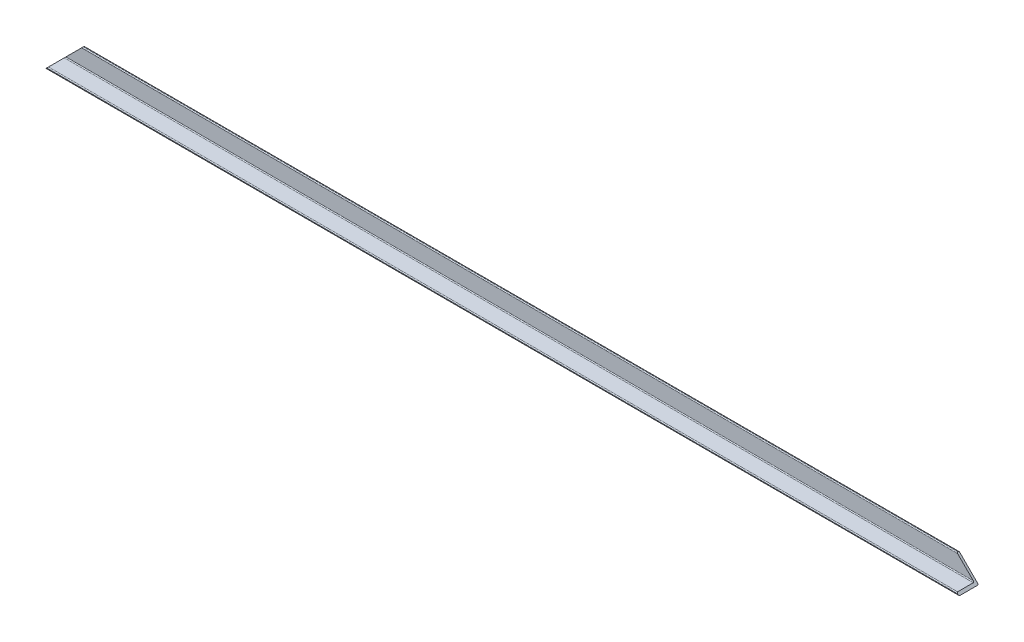
SolidWorks part; units mm, degrees
ref_plane "Front Plane" through (0, 0, 0) normal (0, 0, 1) x (1, 0, 0)
ref_plane "Top Plane" through (0, 0, 0) normal (0, 1, 0) x (1, 0, 0)
ref_plane "Right Plane" through (0, 0, 0) normal (1, 0, 0) x (0, 0, -1)
sketch "Sketch1" plane through (0, 0, 0) normal (0, 1, 0) x (1, 0, 0)
  line L1 (-532.5, 11.25) -> (532.5, 11.25)
  line L2 (-532.5, 11.25) -> (-532.5, -11.25)
  line L3 (-532.5, -11.25) -> (532.5, -11.25)
  line L4 (532.5, 11.25) -> (532.5, -11.25)
  line L5 (-532.5, 11.25) -> (532.5, -11.25) construction
  line L6 (-532.5, -11.25) -> (532.5, 11.25) construction
  point P0 (0, 0)
  dimension "D1" = 1065
  dimension "D2" = 22.5
extrude "Boss-Extrude1" add sketch "Sketch1" along normal blind 2.5
sketch "Sketch2" plane through (0, 2.5, 0) normal (0, 1, 0) x (1, 0, 0)
  line L0 (532.5, -11.25) -> (532.5, 11.25) construction
  line L1 (-532.5, 11.25) -> (532.5, 11.25)
  line L2 (-532.5, 11.25) -> (-532.5, 8.75)
  line L3 (-532.5, 8.75) -> (532.5, 8.75)
  line L4 (532.5, 11.25) -> (532.5, 8.75)
  dimension "D1" = 2.5
extrude "Boss-Extrude2" add sketch "Sketch2" along normal blind 20
sketch "Sketch3" plane through (0, 0, -8.75) normal (0, 0, 1) x (1, 0, 0)
  line L0 (-532.5, 22.5) -> (-532.5, -7.5)
  line L1 (-532.5, 22.5) -> (532.5, 22.5) construction
  line L2 (-532.5, -7.5) -> (-502.5, 22.5)
  line L3 (-502.5, 22.5) -> (-532.5, 22.5)
  line L4 (532.5, 22.5) -> (532.5, -7.5)
  line L5 (532.5, -7.5) -> (502.5, 22.5)
  line L6 (502.5, 22.5) -> (532.5, 22.5)
  point P2 (0, 0)
  dimension "D1" = 30
  dimension "D2" = 30
  dimension "D3" = 45
  dimension "D4" = 45
extrude "Cut-Extrude1" cut sketch "Sketch3" against normal blind 25 and the other way through all
fillet "Fillet2" radius 1 6 edges at (0, 0, -11.25) (0, 0, 11.25) (0, 2.5, 11.25) (0, 22.5, -11.25) (0, 22.5, -8.75) (0, 2.5, -8.75)
